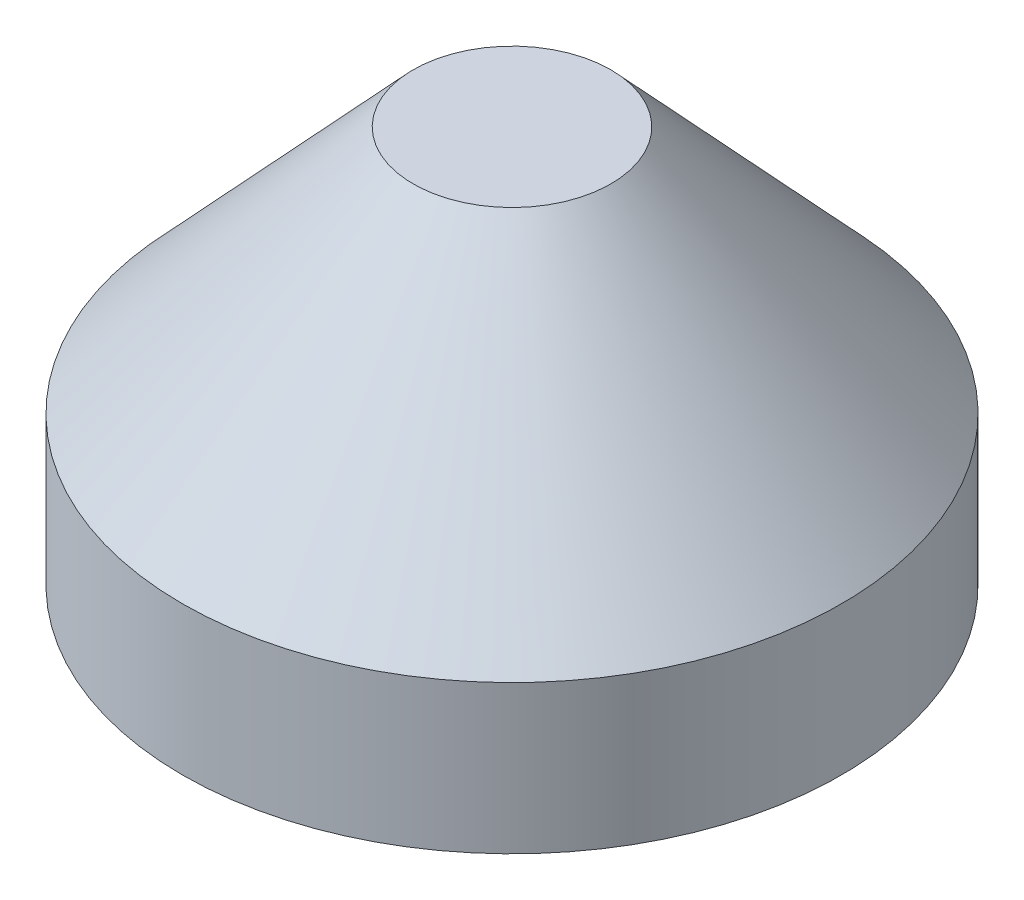
SolidWorks part; units mm, degrees
ref_plane "Front" through (0, 0, 0) normal (0, 0, 1) x (1, 0, 0)
ref_plane "Top" through (0, 0, 0) normal (0, 1, 0) x (1, 0, 0)
ref_plane "Right" through (0, 0, 0) normal (1, 0, 0) x (0, 0, -1)
sketch "Sketch1" plane through (0, 0, 0) normal (0, 0, 1) x (1, 0, 0)
  line L0 (0, 0) -> (0, 7.22)
  line L1 (0, 7.22) -> (-1.8, 7.22)
  line L2 (-1.8, 7.22) -> (-6, 2.7)
  line L3 (-6, 2.7) -> (-6, 0)
  line L4 (-6, 0) -> (0, 0)
  line L5 (0, 0) -> (6, 0)
  line L6 (6, 0) -> (6, 2.7)
  line L7 (6, 2.7) -> (1.8, 7.22)
  line L8 (1.8, 7.22) -> (0, 7.22)
  dimension "D1" = 12
  dimension "D2" = 3.6
  dimension "D3" = 7.22
  dimension "D4" = 2.7
revolve "Revolve1" add sketch "Sketch1" angle 360 about L0
ref_plane "Front nodal plane" through (0, 4.87, 0) normal (0, 1, 0) x (1, 0, 0)
ref_plane "Rear nodal plane" through (0, 3.27, 0) normal (0, -1, 0) x (-1, 0, 0)
